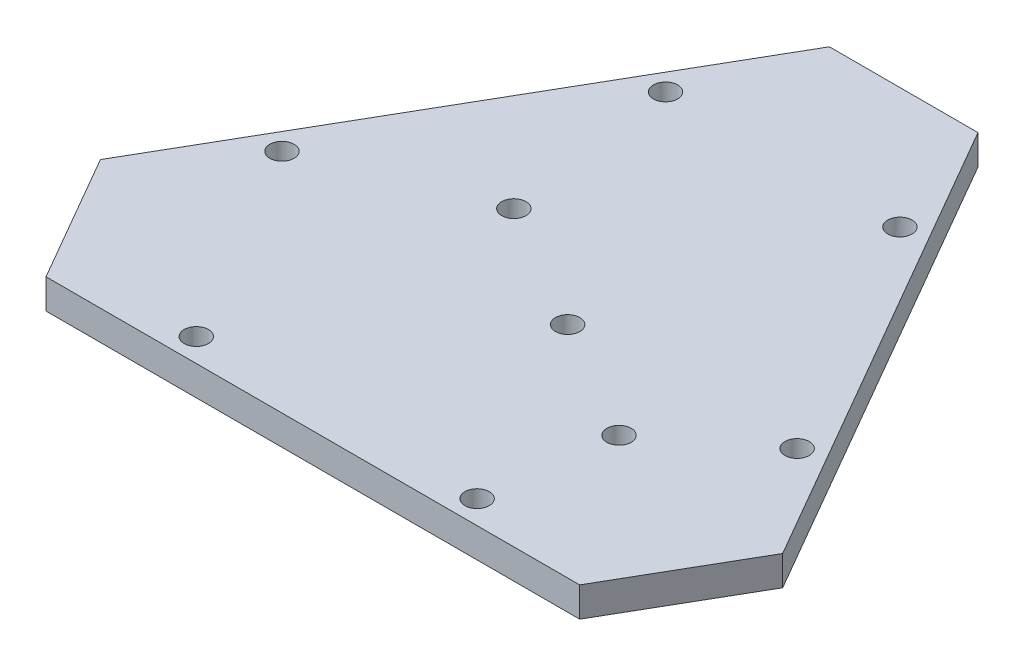
SolidWorks part; units mm, degrees
ref_plane "Front Plane" through (0, 0, 0) normal (0, 0, 1) x (1, 0, 0)
ref_plane "Top Plane" through (0, 0, 0) normal (0, 1, 0) x (1, 0, 0)
ref_plane "Right Plane" through (0, 0, 0) normal (1, 0, 0) x (0, 0, -1)
sketch "Sketch1" plane through (0, 0, 0) normal (0, 1, 0) x (1, 0, 0)
  line L0 (-64.9519, -37.5) -> (0, 0) construction
  line L1 (0, 0) -> (64.9519, -37.5) construction
  line L2 (0, 0) -> (0, 75) construction
  line L3 (-15.875, 75) -> (15.875, 75)
  line L4 (57.0144, -51.2482) -> (72.8894, -23.7518)
  line L5 (-57.0144, -51.2482) -> (-72.8894, -23.7518)
  line L6 (-15.875, 75) -> (-72.8894, -23.7518)
  line L7 (-57.0144, -51.2482) -> (57.0144, -51.2482)
  line L8 (72.8894, -23.7518) -> (15.875, 75)
  point P11 (64.9519, -37.5)
  point P12 (-64.9519, -37.5)
  dimension "D3" = 75
  dimension "D1" = 120
  dimension "D2" = 120
  dimension "D4" = 31.75
  dimension "D5" = 114.0288
  dimension "D6" = 114.0288
  dimension "D7" = 114.0288
extrude "Boss-Extrude1" add sketch "Sketch1" along normal blind 6.35
sketch "Sketch9" plane through (0, 6.35, 0) normal (0, 1, 0) x (1, 0, 0)
  line L0 (-25.0303, 49.1428) -> (-29.3414, 51.6755)
  line L1 (-15.875, 75) -> (-72.8894, -23.7518) construction
  line L2 (-55.0302, -2.8188) -> (-59.3603, -0.3188)
  line L10 (-15.875, 75) -> (-9.7477, 75)
  line L11 (15.875, 75) -> (-15.875, 75) construction
  line L13 (25.0086, 49.1802) -> (29.3387, 51.6802)
  line L14 (72.8894, -23.7518) -> (15.875, 75) construction
  line L16 (55.0087, -2.7812) -> (59.3603, -0.3188)
  line L20 (-29.9012, -46.2482) -> (-29.9012, -51.2482)
  line L21 (-57.0144, -51.2482) -> (57.0144, -51.2482) construction
  line L22 (30.0988, -46.2482) -> (30.0988, -51.2482)
  circle A0 centre (-29.9012, -46.2482) radius 2.6
  circle A1 centre (30.0988, -46.2482) radius 2.6
  circle A2 centre (25.0086, 49.1802) radius 2.6
  circle A4 centre (55.0087, -2.7812) radius 2.6
  circle A5 centre (-55.0302, -2.8188) radius 2.6
  circle A6 centre (-25.0303, 49.1428) radius 2.6
  dimension "D2" = 5
  dimension "D1" = 5.2
  dimension "D4" = 60
  dimension "D5" = 5.2
  dimension "D6" = 5.2
  dimension "D3" = 5
  dimension "D7" = 5.2
  dimension "D12" = 5.2
  dimension "D8" = 5
  dimension "D9" = 5
  dimension "D10" = 60
  dimension "D11" = 5
  dimension "D13" = 5
  dimension "D14" = 60
extrude "Cut-Extrude1" cut sketch "Sketch9" against normal through all contours A6 | A2 | A4 | A1 | A5 | A0
sketch "Sketch12" plane through (0, 6.35, 0) normal (0, 1, 0) x (1, 0, 0)
  circle A0 centre (33.5393, -19.3639) radius 2.6
  circle A1 centre (7.5585, -4.3639) radius 2.6
  circle A2 centre (-19.6386, 11.3384) radius 2.6
  dimension "D1" = 5.2
  dimension "D2" = 5.2
  dimension "D3" = 5.2
  dimension "D4" = 30
  dimension "D5" = 31.4045
extrude "Cut-Extrude4" cut sketch "Sketch12" against normal through all
